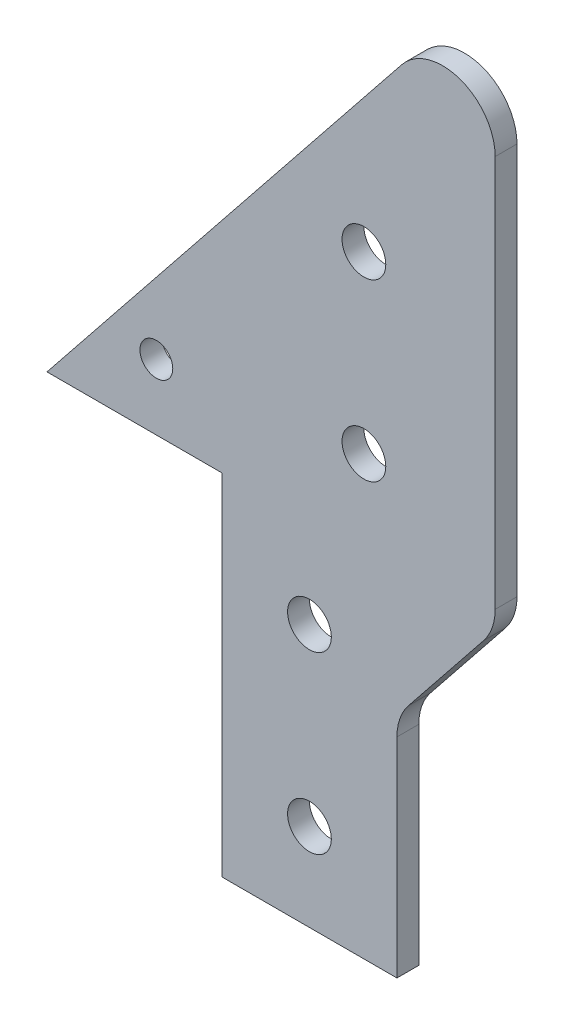
SolidWorks part; units mm, degrees
material "6063-T1"
ref_plane "Front Plane" through (0, 0, 0) normal (0, 0, 1) x (1, 0, 0)
ref_plane "Top Plane" through (0, 0, 0) normal (0, 1, 0) x (1, 0, 0)
ref_plane "Right Plane" through (0, 0, 0) normal (1, 0, 0) x (0, 0, -1)
sketch "Sketch1" plane through (0, 0, 0) normal (0, 0, 1) x (1, 0, 0)
  line L0 (0, 0) -> (406.4, 508)
  line L1 (406.4, 508) -> (406.4, 426.6803)
  line L2 (406.4, 426.6803) -> (65.0557, 0)
  line L3 (65.0557, 0) -> (0, 0)
  line L4 (65.0557, 0) -> (50.8, -17.8197)
  line L5 (25.4, -50.8) -> (65.0557, -50.8)
  line L6 (25.4, -50.8) -> (25.4, 173.2632)
  line L7 (25.4, 173.2632) -> (65.0557, 173.2632)
  line L8 (65.0557, -50.8) -> (65.0557, 173.2632)
  line L9 (25.4, -50.8) -> (50.8, -50.8)
  line L10 (25.4, -50.8) -> (25.4, 0)
  line L11 (25.4, 0) -> (50.8, 0)
  line L12 (50.8, -50.8) -> (50.8, 0)
  circle A0 centre (38.1, -38.1) radius 3.175
  circle A1 centre (38.1, -12.7) radius 3.175
  circle A2 centre (46.0057, 12.7) radius 3.175
  circle A3 centre (46.0057, 38.1) radius 3.175
  circle A4 centre (15.875, 9.525) radius 2.3813
  dimension "D6" = 6.35
  dimension "D7" = 6.35
  dimension "D15" = 6.35
  dimension "D16" = 6.35
  dimension "D20" = 4.7625
  dimension "D1" = 406.4
  dimension "D2" = 508
  dimension "D3" = 50.8
  dimension "D4" = 25.4
  dimension "D5" = 50.8
  dimension "D8" = 12.7
  dimension "D9" = 25.4
  dimension "D10" = 12.7
  dimension "D11" = 12.7
  dimension "D12" = 19.05
  dimension "D13" = 12.7
  dimension "D14" = 38.1
  dimension "D17" = 25.4
  dimension "D18" = 9.525
  dimension "D19" = 9.525
extrude "Boss-Extrude1" add sketch "Sketch1" along normal blind 3.175 contours L3 L8 L0 L6 A3 A2 | L5 L12 L3 L6 A1 A0 | L12 L4 L3 | L3 L6 L0
fillet "Fillet1" radius 7.62 3 edges at (50.8, -17.8197, 1.5875) (65.0557, 0, 1.5875) (65.0557, 81.3197, 1.5875)
